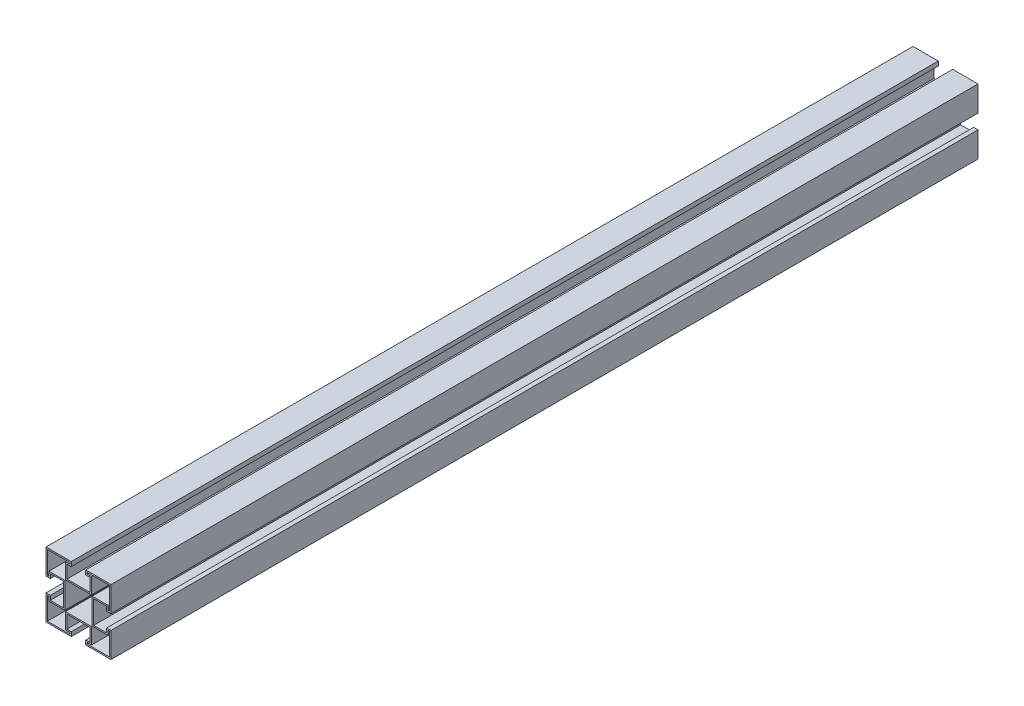
SolidWorks part; units mm, degrees
ref_plane "Ön Düzlem" through (0, 0, 0) normal (0, 0, 1) x (1, 0, 0)
ref_plane "Üst Düzlem" through (0, 0, 0) normal (0, 1, 0) x (1, 0, 0)
ref_plane "Sağ Düzlem" through (0, 0, 0) normal (1, 0, 0) x (0, 0, -1)
sketch "Sketch1" plane through (0, 0, 0) normal (0, 0, 1) x (1, 0, 0)
  line L0 (-5, 22.5) -> (-5, 19.5)
  line L1 (22.5, 22.5) -> (5, 22.5)
  line L2 (22.5, 22.5) -> (22.5, 5)
  line L3 (22.5, -22.5) -> (5, -22.5)
  line L4 (-22.5, 22.5) -> (-22.5, 5)
  line L5 (22.5, 22.5) -> (-22.5, -22.5) construction
  line L6 (22.5, -22.5) -> (-22.5, 22.5) construction
  line L7 (-5, 19.5) -> (-8, 19.5)
  line L8 (-8, 19.5) -> (-8, 10.5)
  line L9 (-8, 10.5) -> (8, 10.5)
  line L10 (8, 10.5) -> (8, 19.5)
  line L11 (8, 19.5) -> (5, 19.5)
  line L12 (5, 19.5) -> (5, 22.5)
  line L13 (22.5, 5) -> (19.5, 5)
  line L14 (19.5, 5) -> (19.5, 8)
  line L15 (19.5, 8) -> (10.5, 8)
  line L16 (10.5, 8) -> (10.5, -8)
  line L17 (10.5, -8) -> (19.5, -8)
  line L18 (19.5, -8) -> (19.5, -5)
  line L19 (19.5, -5) -> (22.5, -5)
  line L20 (0, 0) -> (22.5, 0) construction
  line L21 (0, 22.5) -> (0, 0) construction
  line L22 (-19.5, 5) -> (-19.5, 8)
  line L23 (-10.5, 8) -> (-10.5, -8)
  line L24 (-19.5, -8) -> (-19.5, -5)
  line L25 (-10.5, -8) -> (-19.5, -8)
  line L26 (-19.5, -5) -> (-22.5, -5)
  line L27 (-22.5, 5) -> (-19.5, 5)
  line L28 (-19.5, 8) -> (-10.5, 8)
  line L29 (-5, -22.5) -> (-5, -19.5)
  line L30 (5, -19.5) -> (5, -22.5)
  line L31 (8, -19.5) -> (5, -19.5)
  line L32 (8, -10.5) -> (8, -19.5)
  line L33 (-8, -10.5) -> (8, -10.5)
  line L34 (-8, -19.5) -> (-8, -10.5)
  line L35 (-5, -19.5) -> (-8, -19.5)
  line L36 (-5, -22.5) -> (-22.5, -22.5)
  line L37 (22.5, -5) -> (22.5, -22.5)
  line L38 (-5, 22.5) -> (-22.5, 22.5)
  line L39 (-22.5, -5) -> (-22.5, -22.5)
  line L40 (-5, 22.5) -> (5, 22.5) construction
  line L41 (22.5, 5) -> (22.5, -5) construction
  line L42 (-6, 21.5) -> (-21.5, 21.5)
  line L43 (-21.5, 21.5) -> (-21.5, 6)
  line L44 (-21.5, 6) -> (-20.5, 6)
  line L45 (-20.5, 6) -> (-20.5, 9)
  line L46 (-20.5, 9) -> (-9.5, 9)
  line L47 (-9.5, 9) -> (-9.5, -9)
  line L48 (-9.5, -9) -> (-20.5, -9)
  line L49 (-20.5, -9) -> (-20.5, -6)
  line L50 (-20.5, -6) -> (-21.5, -6)
  line L51 (-21.5, -6) -> (-21.5, -21.5)
  line L52 (-6, -21.5) -> (-21.5, -21.5)
  line L53 (-6, -21.5) -> (-6, -20.5)
  line L54 (-6, -20.5) -> (-9, -20.5)
  line L55 (-9, -20.5) -> (-9, -9.5)
  line L56 (-9, -9.5) -> (9, -9.5)
  line L57 (9, -9.5) -> (9, -20.5)
  line L58 (9, -20.5) -> (6, -20.5)
  line L59 (6, -20.5) -> (6, -21.5)
  line L60 (21.5, -21.5) -> (6, -21.5)
  line L61 (21.5, -6) -> (21.5, -21.5)
  line L62 (20.5, -6) -> (21.5, -6)
  line L63 (20.5, -9) -> (20.5, -6)
  line L64 (9.5, -9) -> (20.5, -9)
  line L65 (9.5, 9) -> (9.5, -9)
  line L66 (20.5, 9) -> (9.5, 9)
  line L67 (20.5, 6) -> (20.5, 9)
  line L68 (21.5, 6) -> (20.5, 6)
  line L69 (21.5, 21.5) -> (21.5, 6)
  line L70 (21.5, 21.5) -> (6, 21.5)
  line L71 (6, 20.5) -> (6, 21.5)
  line L72 (9, 20.5) -> (6, 20.5)
  line L73 (9, 9.5) -> (9, 20.5)
  line L74 (-9, 9.5) -> (9, 9.5)
  line L75 (-9, 20.5) -> (-9, 9.5)
  line L76 (-6, 20.5) -> (-9, 20.5)
  line L77 (-6, 21.5) -> (-6, 20.5)
  point P0 (0, 0)
  dimension "D1" = 45
  dimension "D2" = 3
  dimension "D3" = 10
  dimension "D4" = 10
  dimension "D5" = 12
  dimension "D6" = 12
  dimension "D7" = 1
extrude "Boss-Extrude2" add sketch "Sketch1" along normal mid plane 600 contours L26 L39 L36 L29 L35 L34 L33 L32 L31 L30 L3 L37 L19 L18 L17 L16 L15 L14 L13 L2 L1 L12 L11 L10 L9 L8 L7 L0 L38 L4 L27 L22 L28 L23 L25 L24 L42 L77 L76 L75 L74 L73 L72 L71 L70 L69 L68 L67 L66 L65
sketch "Sketch2" plane through (0, 22.5, 0) normal (0, 1, 0) x (1, 0, 0)
  line L0 (0, 300) -> (0, -300) construction
  line L1 (-8, 300) -> (8, 300) construction
  line L2 (-8, -300) -> (8, -300) construction
ref_plane "Plane1" through (0, 0, 0) normal (-1, 0, 0) x (0, 0, 1)
sketch "Sketch3" plane through (-22.5, 0, 0) normal (-1, 0, 0) x (0, 0, 1)
  line L0 (300, 0) -> (-300, 0) construction
  line L1 (300, 8) -> (300, -8) construction
  line L2 (-300, 8) -> (-300, -8) construction
sketch "Sketch4" plane through (22.5, 0, 0) normal (1, 0, 0) x (0, 0, -1)
  line L0 (300, 0) -> (-300, 0) construction
ref_plane "Plane2" through (0, 0, 0) normal (0, 1, 0) x (1, 0, 0)
ref_plane "Plane3" through (0, 0, 0) normal (0, 1, 0) x (1, 0, 0)
